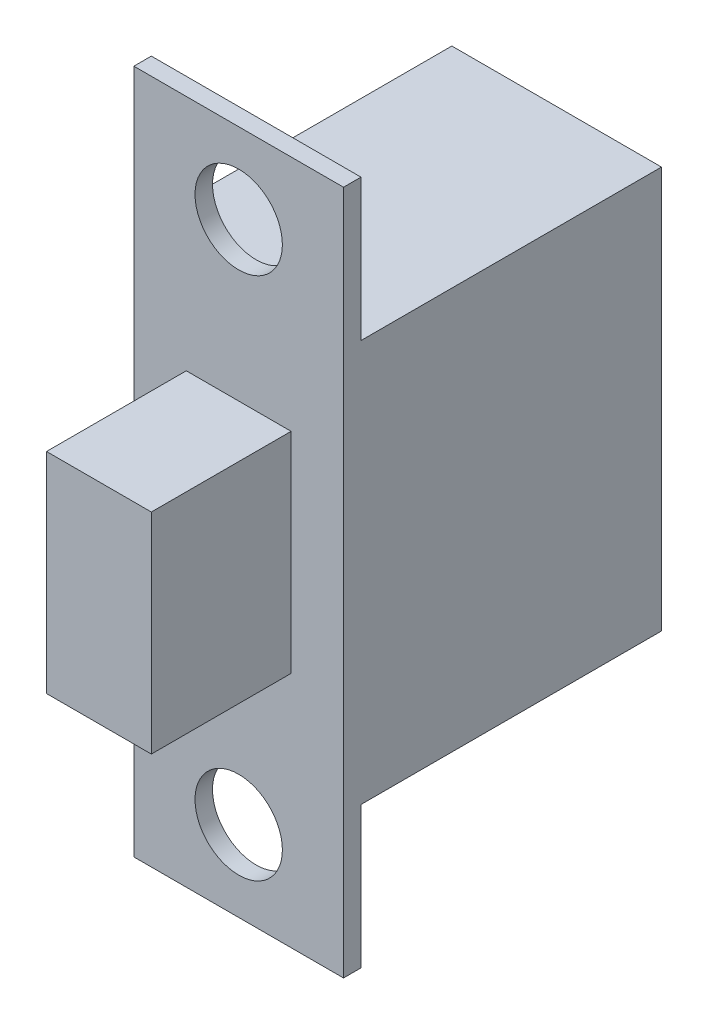
SolidWorks part; units mm, degrees
ref_plane "Front Plane" through (0, 0, 0) normal (0, 0, 1) x (1, 0, 0)
ref_plane "Top Plane" through (0, 0, 0) normal (0, 1, 0) x (1, 0, 0)
ref_plane "Right Plane" through (0, 0, 0) normal (1, 0, 0) x (0, 0, -1)
sketch "Sketch1" plane through (0, 0, 0) normal (0, 0, 1) x (1, 0, 0)
  line L1 (18.1258, 10.7529) -> (24.1258, 10.7529)
  line L2 (18.1258, 10.7529) -> (18.1258, -8.8471)
  line L3 (18.1258, -8.8471) -> (24.1258, -8.8471)
  line L4 (24.1258, 10.7529) -> (24.1258, -8.8471)
  dimension "D1" = 19.6
  dimension "D2" = 6
extrude "Boss-Extrude1" add sketch "Sketch1" along normal blind 0.5
sketch "Sketch2" plane through (0, 0, 0) normal (0, 0, -1) x (-1, 0, 0)
  line L1 (-18.1258, -8.8471) -> (-24.1258, -8.8471) construction
  line L2 (-24.1258, -8.8471) -> (-24.1258, 10.7529) construction
  circle A0 centre (-21.1258, 8.4529) radius 1.25
  circle A1 centre (-21.1258, -6.5471) radius 1.25
  point P6 (0, 0)
  point P7 (0, 0)
  dimension "D1" = 15
  dimension "D2" = 2.3
  dimension "D3" = 3
  dimension "D4" = 3
extrude "Cut-Extrude1" cut sketch "Sketch2" against normal blind 1
sketch "Sketch3" plane through (0, 0, 0.5) normal (0, 0, 1) x (1, 0, 0)
  line L0 (18.1258, 10.7529) -> (18.1258, -8.8471) construction
  line L1 (18.1258, 6.7029) -> (24.1258, 6.7029)
  line L2 (18.1258, 6.7029) -> (18.1258, -4.7971)
  line L3 (18.1258, -4.7971) -> (24.1258, -4.7971)
  line L4 (24.1258, 6.7029) -> (24.1258, -4.7971)
  line L5 (24.1258, 10.7529) -> (18.1258, 10.7529) construction
  dimension "D1" = 11.5
  dimension "D2" = 6
  dimension "D3" = 0
  dimension "D4" = 4.05
extrude "Boss-Extrude2" add sketch "Sketch3" against normal blind 9.1 separate body
sketch "Sketch6" plane through (0, 0, 0.5) normal (0, 0, 1) x (1, 0, 0)
  line L0 (24.1258, -8.8471) -> (24.1258, 10.7529) construction
  line L1 (19.6258, 3.9529) -> (22.6258, 3.9529)
  line L2 (19.6258, 3.9529) -> (19.6258, -2.0471)
  line L3 (19.6258, -2.0471) -> (22.6258, -2.0471)
  line L4 (22.6258, 3.9529) -> (22.6258, -2.0471)
  line L5 (24.1258, 6.7029) -> (18.1258, 6.7029) construction
  point P8 (21.1258, 6.7029)
  dimension "D1" = 3
  dimension "D2" = 1.5
  dimension "D3" = 6
  dimension "D4" = 2.75
extrude "Boss-Extrude3" add sketch "Sketch6" along normal blind 4
